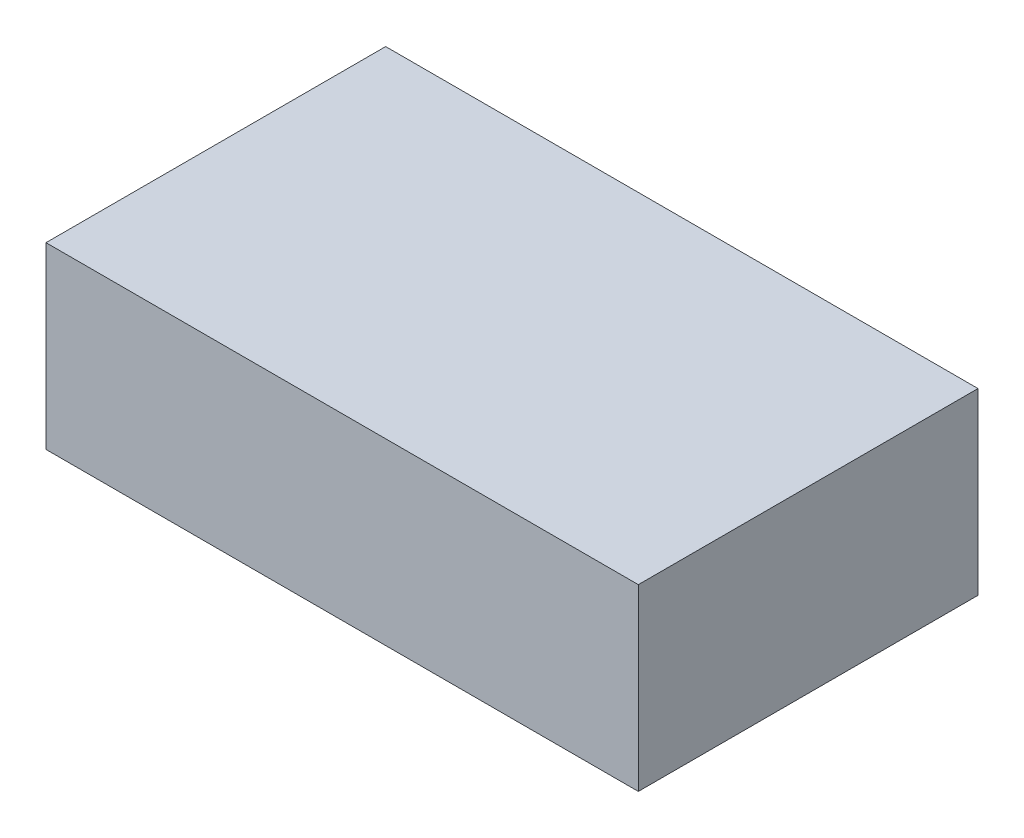
SolidWorks part; units mm, degrees
ref_plane "Front" through (0, 0, 0) normal (0, 0, 1) x (1, 0, 0)
ref_plane "Top" through (0, 0, 0) normal (0, 1, 0) x (1, 0, 0)
ref_plane "Right" through (0, 0, 0) normal (1, 0, 0) x (0, 0, -1)
sketch "Sketch1" plane through (0, 0, 0) normal (0, 1, 0) x (1, 0, 0)
  line L1 (-23.35, -13.39) -> (23.35, -13.39)
  line L2 (-23.35, -13.39) -> (-23.35, 13.39)
  line L3 (-23.35, 13.39) -> (23.35, 13.39)
  line L4 (23.35, -13.39) -> (23.35, 13.39)
  line L5 (-23.35, -13.39) -> (23.35, 13.39) construction
  line L6 (-23.35, 13.39) -> (23.35, -13.39) construction
  point P0 (0, 0)
  dimension "D1" = 46.7
  dimension "D2" = 26.78
extrude "Boss-Extrude1" add sketch "Sketch1" along normal blind 14.12
